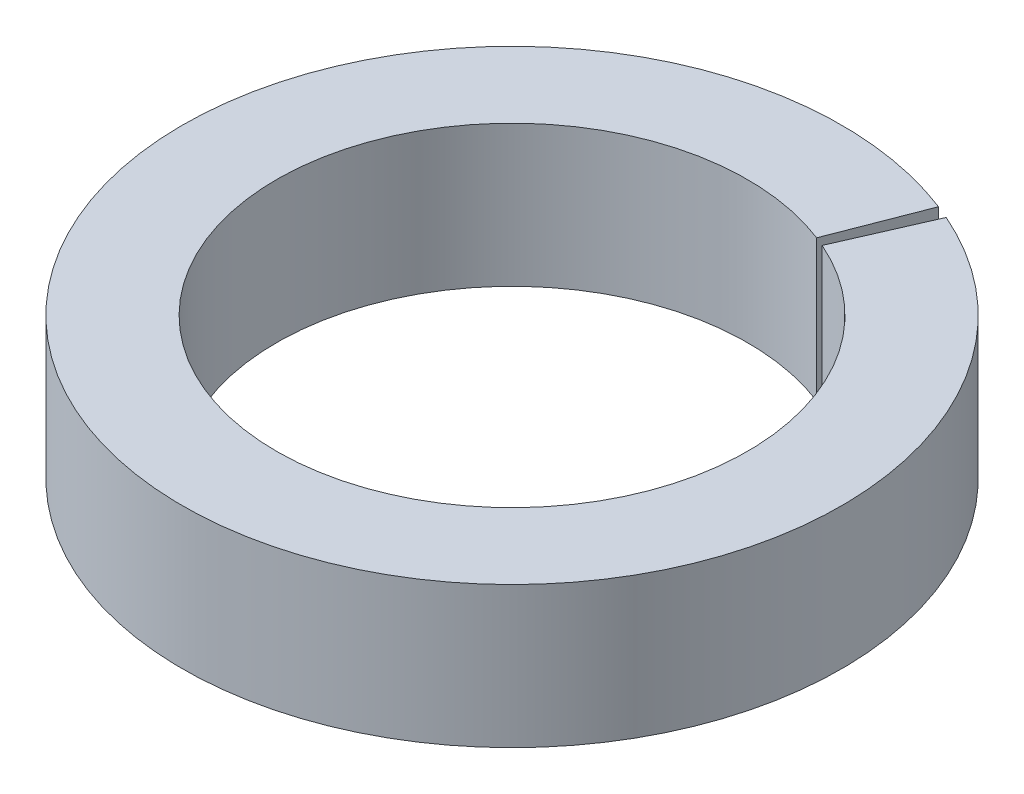
SolidWorks part; units mm, degrees
ref_plane "Front Plane" through (0, 0, 0) normal (0, 0, 1) x (1, 0, 0)
ref_plane "Top Plane" through (0, 0, 0) normal (0, 1, 0) x (1, 0, 0)
ref_plane "Right Plane" through (0, 0, 0) normal (1, 0, 0) x (0, 0, -1)
sketch "Sketch1" plane through (0, 0, 0) normal (0, 1, 0) x (1, 0, 0)
  line L0 (16.0629, 41.4462) -> (11.4735, 29.6044)
  line L1 (17.8329, 40.716) -> (12.7378, 29.0828)
  arc A0 (16.0629, 41.4462) -> (17.8329, 40.716) centre (0, 0) ccw
  arc A1 (11.4735, 29.6044) -> (12.7378, 29.0828) centre (0, 0) ccw
  dimension "D1" = 63.5
  dimension "D2" = 88.9
extrude "Boss-Extrude1" add sketch "Sketch1" along normal blind 19.05
